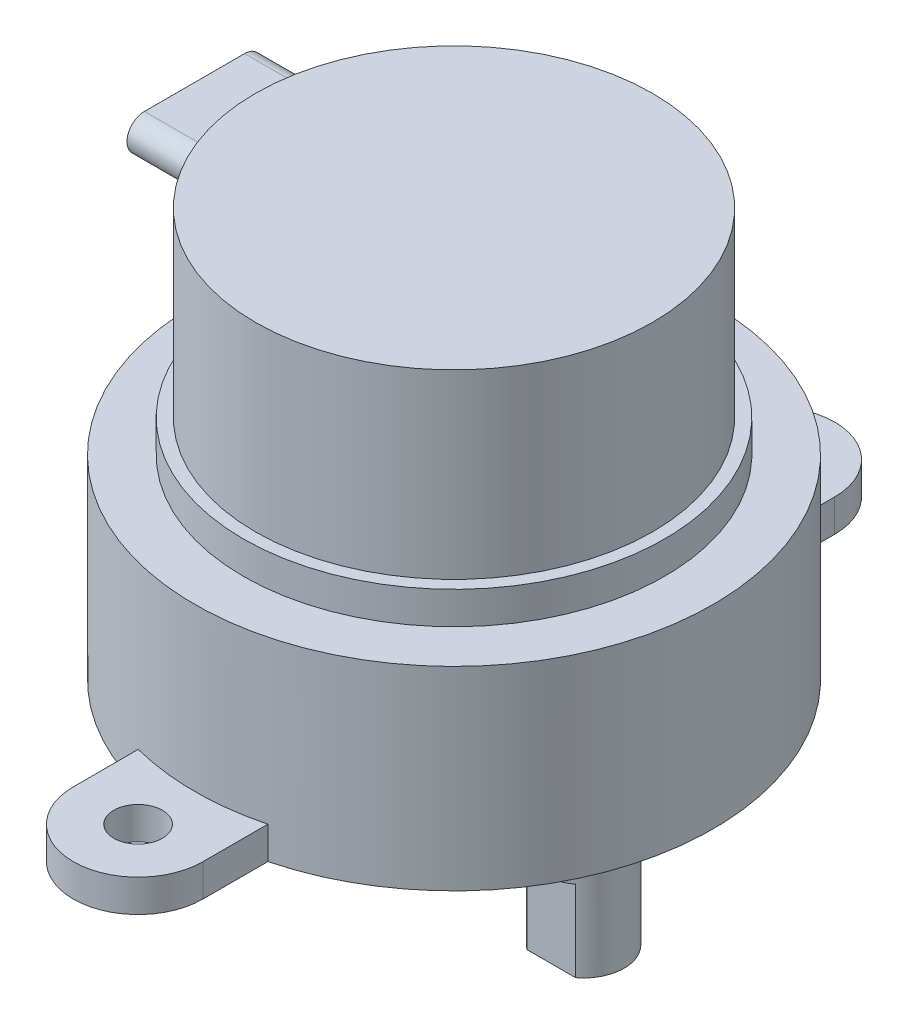
SolidWorks part; units mm, degrees
ref_plane "前视基准面" through (0, 0, 0) normal (0, 0, 1) x (1, 0, 0)
ref_plane "上视基准面" through (0, 0, 0) normal (0, 1, 0) x (1, 0, 0)
ref_plane "右视基准面" through (0, 0, 0) normal (1, 0, 0) x (0, 0, -1)
sketch "草图1" plane through (0, 0, 0) normal (0, 0, 1) x (1, 0, 0)
  line L0 (0, 0) -> (-16, 0)
  line L1 (-16, 0) -> (-16, 12)
  line L2 (-16, 12) -> (-13, 12)
  line L3 (-13, 12) -> (-13, 14)
  line L4 (-13, 14) -> (-12.25, 14)
  line L5 (-12.25, 14) -> (-12.25, 25.2)
  line L6 (-12.25, 25.2) -> (0, 25.2)
  line L7 (0, -7.0565) -> (0, 33.6877) construction
  line L8 (-25.5947, 0) -> (24.4784, 0) construction
  line L9 (0, 0) -> (0, 25.2)
  point P15 (0, 26.1121)
  dimension "D1" = 12
  dimension "D2" = 32
  dimension "D3" = 26
  dimension "D4" = 2
  dimension "D5" = 25.2
  dimension "D6" = 24.5
revolve "旋转1" add sketch "草图1" angle 360 about L9
sketch "草图2" plane through (0, 0, 0) normal (0, 0, 1) x (1, 0, 0)
  line L0 (3.5, 0) -> (3.5, -1.25)
  line L1 (-16, 0) -> (16, 0) construction
  line L2 (3.5, -1.25) -> (4, -1.25)
  line L3 (4, -1.25) -> (4, -2.7)
  line L4 (4, -2.7) -> (5.5, -2.7)
  line L5 (5.5, -2.7) -> (5.5, -10.2)
  line L6 (5.5, -10.2) -> (8, -10.2)
  line L7 (8, -10.2) -> (8, 0) construction
  line L8 (8, 0) -> (3.5, 0)
  line L9 (8, -10.2) -> (8, 0)
  dimension "D1" = 1.25
  dimension "D2" = 2.7
  dimension "D3" = 5
  dimension "D4" = 8
  dimension "D5" = 9
  dimension "D6" = 10.2
  dimension "D7" = 8
revolve "旋转2" add sketch "草图2" angle 360 about L7
hole_wizard "M3 螺纹孔1" positions "草图3" profile "草图4" tap size "M3" standard "GB"
sketch "草图3" plane through (0, -10.2, 0) normal (0, -1, 0) x (-1, 0, 0)
  point P0 (-8, 0)
cosmetic thread "孔螺蚊线1" parameters "D2"=3
sketch "草图4" plane through (8, -10.2, 0) normal (1, 0, 0) x (0, 0, -1)
  line L0 (0, 0) -> (0, 5.7511)
  line L1 (0, 5.7511) -> (1.25, 5)
  line L2 (1.25, 5) -> (1.25, 0)
  line L5 (1.25, 0) -> (0, 0)
  line L10 (0, 5.7511) -> (-1.25, 5) construction
  line L11 (0, -6.35) -> (0, 107.95) construction
  dimension "螺纹孔钻头直径" = 2.5
  dimension "螺纹孔钻头深度" = 5
  dimension "导头角度" = 118
sketch "草图5" plane through (0, -10.2, 0) normal (0, -1, 0) x (1, 0, 0)
  line L0 (8, 0) -> (17.2139, 0) construction
  line L2 (3.4102, 5.5516) -> (14.0406, 5.5516)
  line L3 (3.4102, 5.5516) -> (3.4102, 2)
  line L4 (3.4102, 2) -> (14.0406, 2)
  line L5 (14.0406, 5.5516) -> (14.0406, 2)
  line L6 (3.9697, -5.065) -> (15.5488, -5.065)
  line L7 (3.9697, -5.065) -> (3.9697, -2)
  line L8 (3.9697, -2) -> (15.5488, -2)
  line L9 (15.5488, -5.065) -> (15.5488, -2)
  dimension "D1" = 4
extrude "切除-拉伸1" cut sketch "草图5" against normal blind 5
sketch "草图6" plane through (0, 0, 0) normal (0, -1, 0) x (1, 0, 0)
  line L0 (0, 0) -> (0, 9.2891) construction
  line L1 (0, -19.5) -> (0, 19.5) construction
  line L2 (-4, -19.5) -> (-4, 19.5)
  line L3 (4, -19.5) -> (4, 19.5)
  arc A0 (-4, -19.5) -> (4, -19.5) centre (0, -19.5) ccw
  arc A1 (4, 19.5) -> (-4, 19.5) centre (0, 19.5) ccw
  circle A2 centre (0, -19.5) radius 1.5
  circle A3 centre (0, 19.5) radius 1.5
  point P5 (0, 0)
  dimension "D1" = 8
  dimension "D3" = 3
  dimension "D2" = 39
extrude "凸台-拉伸1" add sketch "草图6" against normal blind 2
sketch "草图7" plane through (0, 0, 0) normal (1, 0, 0) x (0, 0, -1)
  line L0 (0, 25.2) -> (0, 20.4626) construction
  line L1 (12.25, 25.2) -> (-12.25, 25.2) construction
  line L2 (3.8195, 22.8313) -> (-3.7519, 22.8313) construction
  line L3 (3.0759, 22.8313) -> (-3.1097, 22.8313) construction
  line L4 (3.0759, 21.7523) -> (-3.1097, 21.7523)
  line L5 (3.0759, 23.9102) -> (-3.1097, 23.9102)
  arc A0 (3.0759, 21.7523) -> (3.0759, 23.9102) centre (3.0759, 22.8313) ccw
  arc A1 (-3.1097, 23.9102) -> (-3.1097, 21.7523) centre (-3.1097, 22.8313) ccw
  point P9 (-0.0169, 22.8313)
  point P14 (0, 0)
extrude "凸台-拉伸2" add sketch "草图7" against normal blind 16
